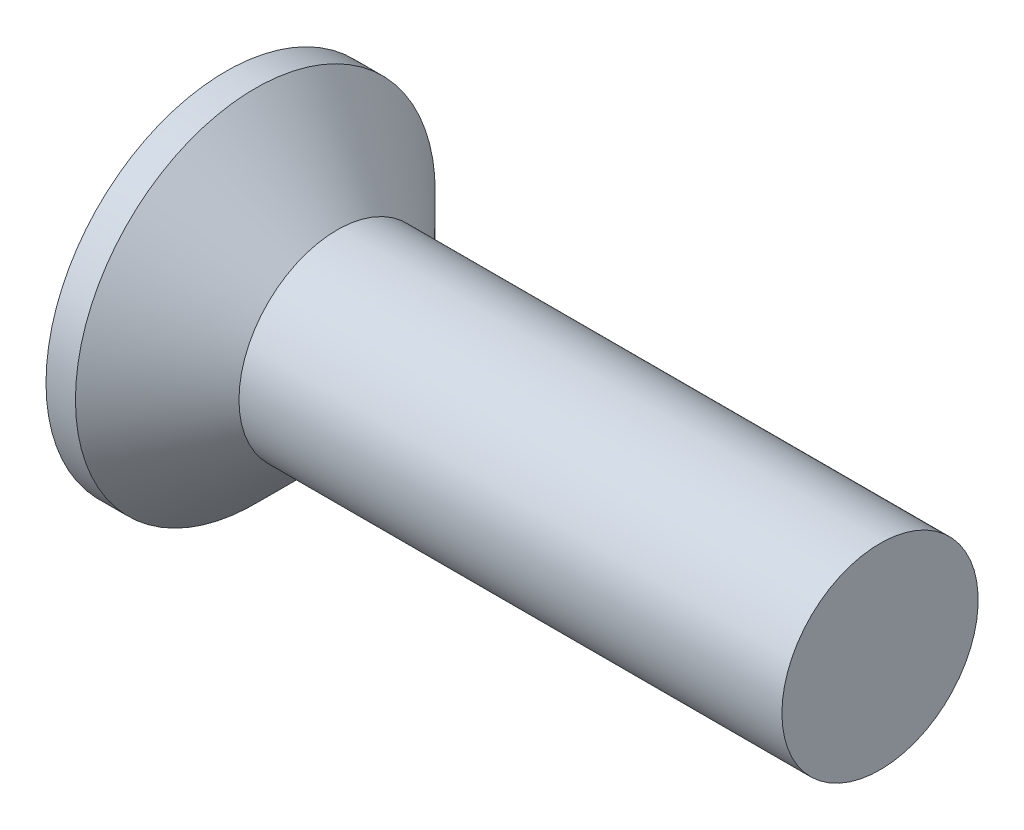
SolidWorks part; units mm, degrees
revolve "Base-Revolve" add sketch "BodySke" angle 360 about L5
sketch "BodySke" plane through (0, 0, 0) normal (0, 0, 1) x (1, 0, 0)
  line L0 (0, 0) -> (0, 2.75)
  line L1 (0, 2.75) -> (0.45, 2.75)
  line L2 (1.7, 1.5) -> (10, 1.5)
  line L3 (10, 1.5) -> (10, 0)
  line L4 (10, 0) -> (0, 0)
  line L5 (-6.35, 0) -> (82.55, 0) construction
  line L6 (1.7, -1.5) -> (10, -1.5) construction
  line L7 (0.45, -2.75) -> (1.7, -1.5) construction
  line L8 (0.45, 2.75) -> (1.7, 1.5)
  line L9 (0, -2.75) -> (0.45, -2.75) construction
  line L10 (2.2, 3.0875) -> (2.2, -6.4375) construction
  line L11 (0, 6.35) -> (0, -3.175) construction
  dimension "Diameter" = 3
  dimension "Length" = 10
  dimension "Head_ht" = 1.7
  dimension "Head_dia" = 5.5
  dimension "Head_ang" = 90
  dimension "D6" = 0.45
  dimension "Advance" = 0.5
  dimension "Thread_nom" = 10
cosmetic thread "ThreadCosmetic" parameters "Thread_length"=7.8, "Thread_minor"=2.439
extrude "Slot" [suppressed] cut sketch "Sketch2" against normal blind 0.9
sketch "Sketch2" plane through (0, 0, 0) normal (-1, 0, 0) x (0, 0, 1)
  line L0 (-2.75, -0.5) -> (2.75, -0.5)
  line L1 (-2.75, -0.5) -> (-2.75, 0.5)
  line L2 (2.75, 0.5) -> (-2.75, 0.5)
  line L3 (2.75, 0.5) -> (2.75, -0.5)
  dimension "Slot_width" = 1
  dimension "D1" = 0.5
  dimension "D2" = 5.5
  dimension "D3" = 2.75
ref_plane "Plane1" through (0, 0, 0) normal (0, 0, 1) x (1, 0, 0)
ref_plane "Plane2" through (0, 0, 0) normal (0, 1, 0) x (1, 0, 0)
ref_plane "Plane3" through (0, 0, 0) normal (1, 0, 0) x (0, 0, -1)
sketch "Sketch3" plane through (0, 0, 0) normal (-1, 0, 0) x (0, 0, 1)
  line L0 (-0.395, 1.55) -> (0.395, 1.55)
  line L1 (0.395, 1.55) -> (0.395, -1.55)
  line L2 (0.395, -1.55) -> (-0.395, -1.55)
  line L3 (-0.395, -1.55) -> (-0.395, 1.55)
  dimension "Cross_dia" = 3.1
  dimension "Cross_width" = 0.79
  dimension "D1" = 1.55
  dimension "D2" = 0.395
ref_plane "Plane4" through (2.08, 0, 0) normal (-1, 0, 0) x (0, 0, 1)
sketch "Sketch4" plane through (2.08, 0, 0) normal (-1, 0, 0) x (0, 0, 1)
  line L0 (-0.1975, 0.1975) -> (0.1975, 0.1975)
  line L3 (0.1975, 0.1975) -> (0.1975, -0.1975)
  line L4 (0.1975, -0.1975) -> (-0.1975, -0.1975)
  line L5 (-0.1975, -0.1975) -> (-0.1975, 0.1975)
  dimension "D2" = 0.395
  dimension "D1" = 0.395
  dimension "D3" = 0.1975
  dimension "D4" = 0.1975
loft "Cross" cut profiles "Sketch3", "Sketch4"
pattern_circular "CirPattern1" count 2 every 90 about axis through (0, 0, 0) along (1, 0, 0) of "Cross"
sketch "ThdSchSke" plane through (0, 0, 0) normal (0, 0, 1) x (1, 0, 0)
  line L0 (2.2, -1.2195) -> (2.0036, -1.5)
  line L1 (2.2, -1.2195) -> (2.3964, -1.5)
  line L2 (2.3964, -1.5) -> (2.3964, -1.875)
  line L3 (-3.175, 0) -> (5.1513, 0) construction
  line L5 (2.3964, -1.875) -> (2.0036, -1.875)
  line L6 (2.0036, -1.875) -> (2.0036, -1.5)
  line L7 (0, 2.75) -> (0, -2.75) construction
  dimension "Diameter" = 3
  dimension "Thread_minor" = 2.439
  dimension "Start" = 2.2
revolve "ThreadSchematic" [suppressed] cut sketch "ThdSchSke" angle 360 about L3
pattern_linear "ThdSchPat" [suppressed]
equation "\"D1@Sketch3\" = \"Cross_dia@Sketch3\" / 2"
equation "\"D2@Sketch3\" = \"Cross_width@Sketch3\" / 2"
equation "\"D1@Sketch4\" = \"Cross_width@Sketch3\" *.5"
equation "\"D2@Sketch4\" = \"D1@Sketch4\""
equation "\"D4@Sketch4\" = \"D2@Sketch4\" / 2"
equation "\"D3@Sketch4\" = \"D1@Sketch4\" / 2"
equation "\"D1@Sketch2\" = \"Slot_width@Sketch2\" / 2"
equation "\"D2@Sketch2\" = \"Head_dia@BodySke\""
equation "\"D3@Sketch2\" = \"D2@Sketch2\" / 2"
equation "\"Thread_length@ThreadCosmetic\" = ((sgn( (\"Length@BodySke\" - \"Advance@BodySke\" - \"Head_ht@BodySke\" ) - \"Thread_nom@BodySke\" )-1)*( (\"Length@BodySke\" - \"Advance@BodySke\" - \"Head_ht@BodySke\" ) - \"Thread_nom@BodySke\" ))/-2+ \"Thread_nom@BodySke\""
equation "\"Thread_minor@ThdSchSke\" = \"Thread_minor@ThreadCosmetic\""
equation "\"Diameter@ThdSchSke\" = \"Diameter@BodySke\""
equation "\"Overcut@ThdSchSke\" = \"Diameter@BodySke\" * 1.25"
equation "\"Start@ThdSchSke\" = 0.000001 + \"Length@BodySke\" - \"Thread_length@ThreadCosmetic\"  '---Countersunk---"
equation "\"Num_threads@ThdSchPat\" = int( \"Thread_length@ThreadCosmetic\" / \"Advance@BodySke\" + 0.999 )  + 1"
equation "\"Advance@ThdSchPat\" = \"Thread_length@ThreadCosmetic\" /  (\"Num_threads@ThdSchPat\" - 1) 'relax it"
